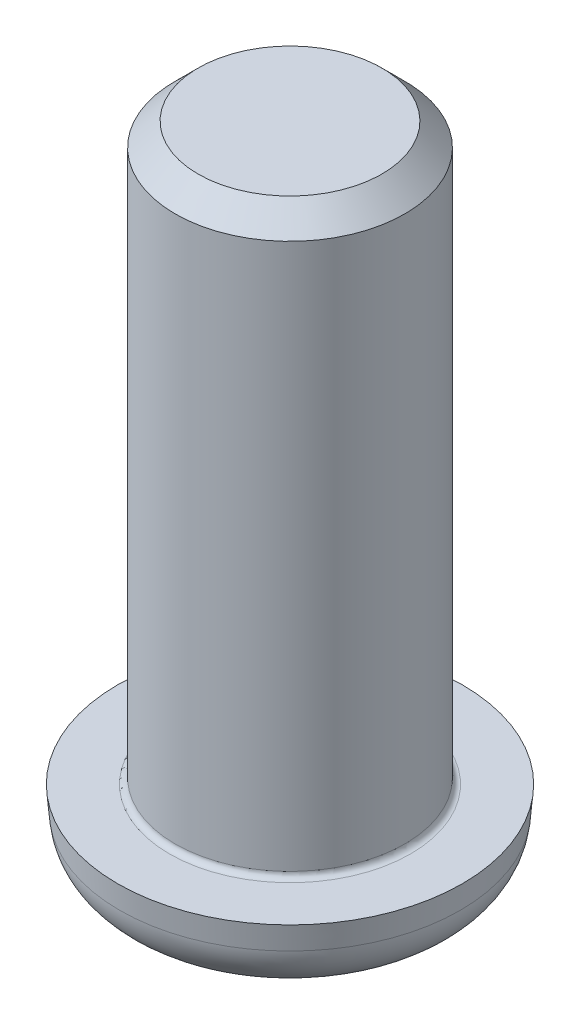
SolidWorks part; units mm, degrees
ref_plane "Front" through (0, 0, 0) normal (0, 0, 1) x (1, 0, 0)
ref_plane "Top" through (0, 0, 0) normal (0, 1, 0) x (1, 0, 0)
ref_plane "Right" through (0, 0, 0) normal (1, 0, 0) x (0, 0, -1)
sketch "Sketch1" plane through (0, 0, 0) normal (1, 0, 0) x (0, 0, -1)
  line L0 (0, 0) -> (0, 1.235) construction
  line L1 (-1, 0) -> (-1, 5)
  line L2 (-1, 5) -> (0, 5)
  line L3 (0, 5) -> (0, -0.6)
  line L4 (0, -0.6) -> (-1.2, -0.6)
  line L5 (-1, 0) -> (-1.5, 0)
  line L6 (-1.5, 0) -> (-1.4816, -0.21)
  line L7 (0, 0) -> (-1, 0) construction
  line L8 (-1.5, 0) -> (-1.5, -1.0829) construction
  arc A0 (-1.4816, -0.21) -> (-1.2, -0.6) centre (-1.0141, -0.1691) ccw
  dimension "d" = 2
  dimension "H" = 0.6
  dimension "D1" = 2.4
  dimension "DD" = 3
  dimension "D2" = 5
  dimension "D3" = 0.39
  dimension "L" = 5
revolve "Revolve1" add sketch "Sketch1" angle 360 about L3
fillet "Fillet5" radius 0.2 1 edges at (0, -0.6, 1.2)
sketch "Sketch2" plane through (0, -0.6, 0) normal (0, -1, 0) x (1, 0, 0)
  line L0 (-2.0062, 0) -> (2.7281, 0) construction
  line L1 (0, 2.3126) -> (0, -2.1951) construction
  line L2 (0.1573, 0.1573) -> (0.925, 0.1573)
  line L3 (-0.1573, 0.925) -> (0.1572, 0.925)
  line L4 (-0.1573, 0.925) -> (-0.1573, 0.1572)
  line L5 (-0.1573, -0.925) -> (0.1573, -0.925)
  line L6 (0.1572, 0.925) -> (0.1573, 0.1573)
  line L7 (-0.925, 0.1572) -> (-0.1573, 0.1572)
  line L8 (-0.925, 0.1572) -> (-0.925, -0.1573)
  line L9 (-0.925, -0.1573) -> (-0.1573, -0.1573)
  line L10 (0.925, 0.1573) -> (0.925, -0.1573)
  line L11 (-0.1573, -0.1573) -> (-0.1573, -0.925)
  line L12 (0.1573, -0.1573) -> (0.925, -0.1573)
  line L13 (0.1573, -0.1573) -> (0.1573, -0.925)
  line L14 (-0.1573, -0.925) -> (-0.1573, -1.325) construction
  dimension "M" = 1.85
  dimension "D2" = 1.85
  dimension "D3" = 0.3145
  dimension "p" = 0.4
extrude "Cut-Extrude1" cut sketch "Sketch2" against normal blind 1.27 draft 3
fillet "Fillet4" radius 0.05 1 edges at (0, 0, 1)
chamfer "Chamfer1" distance 0.2 angle 45 1 edges at (0, 5, 1)
other "Freeze***"
equation "\"D2@Sketch2\" = \"M@Sketch2\""
equation "\"D3@Sketch2\" = \"M@Sketch2\" * 0.17"
equation "\"D1@Sketch1\" = \"DD@Sketch1\" * 0.8"
equation "\"D3@Sketch1\" = \"H@Sketch1\" * 0.65"
equation "\"D1@Chamfer1\" = \"p@Sketch2\" / 2"
